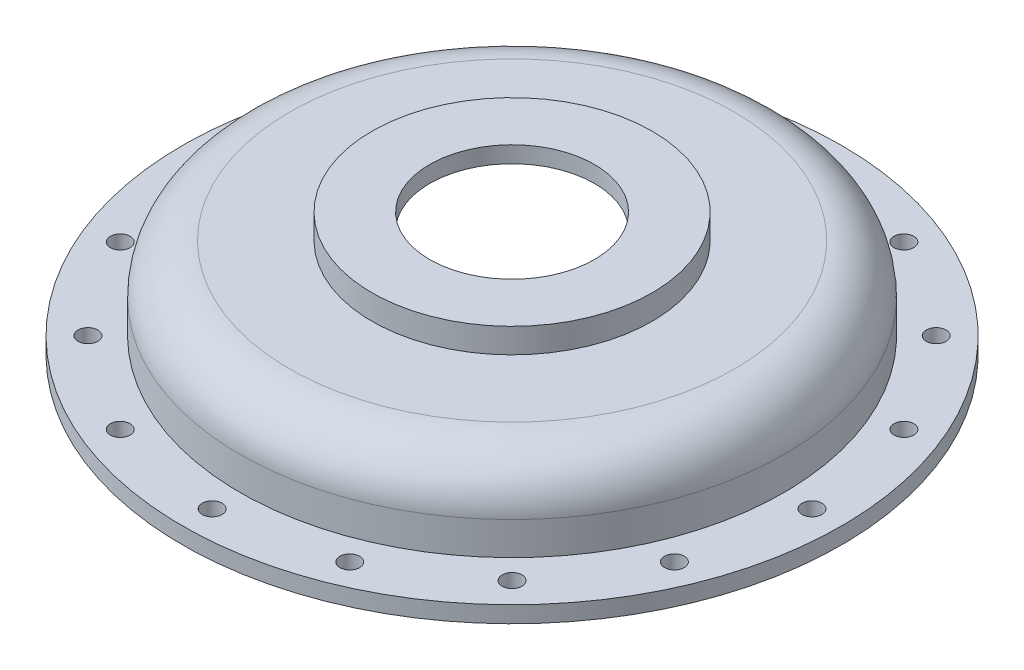
SolidWorks part; units mm, degrees
material "Brass"
ref_plane "Front Plane" through (0, 0, 0) normal (0, 0, 1) x (1, 0, 0)
ref_plane "Top Plane" through (0, 0, 0) normal (0, 1, 0) x (1, 0, 0)
ref_plane "Right Plane" through (0, 0, 0) normal (1, 0, 0) x (0, 0, -1)
sketch "Sketch2" plane through (0, 0, 0) normal (0, 0, 1) x (1, 0, 0)
  line L0 (0, 0) -> (0, 93.3105) construction
  line L1 (155, -56.5685) -> (200, -56.5685)
  line L2 (200, -56.5685) -> (200, -46.5685)
  line L3 (200, -46.5685) -> (165, -46.5685)
  line L4 (165, -46.5685) -> (165, -26.5685)
  line L5 (135, 3.4315) -> (85, 3.4315)
  line L6 (85, 3.4315) -> (85, 18.4315)
  line L7 (85, 18.4315) -> (0, 18.4315)
  line L8 (0, 8.4315) -> (75, 8.4315)
  line L9 (75, -6.5685) -> (75, 8.4315)
  line L10 (75, -6.5685) -> (134.2551, -6.5685)
  line L11 (155, -26.5685) -> (155, -56.5685)
  line L12 (0, 18.4315) -> (0, 8.4315)
  arc A0 (165, -26.5685) -> (135, 3.4315) centre (135, -26.5685) ccw
  arc A1 (134.2551, -6.5685) -> (155, -26.5685) centre (134.2551, -27.3274) cw
  dimension "D1" = 10
  dimension "D2" = 200
  dimension "D7" = 85
  dimension "D11" = 30
  dimension "D9" = 20.7588
  dimension "D3" = 10
  dimension "D4" = 165
  dimension "D5" = 15
  dimension "D6" = 10
  dimension "D8" = 10
  dimension "D10" = 75
  dimension "D12" = 10
revolve "Revolve1" add sketch "Sketch2" angle 360 about L0
sketch "Sketch3" plane through (0, -46.5685, 0) normal (0, 1, 0) x (1, 0, 0)
  circle A0 centre (0, 182) radius 6
  dimension "D2" = 12
  dimension "D1" = 182
extrude "Cut-Extrude1" cut sketch "Sketch3" against normal through all
pattern_circular "CirPattern1" count 16 over 360 about axis through (0, 0, 0) along (0, 1, 0) of "Cut-Extrude1"
sketch "Sketch4" plane through (0, 18.4315, 0) normal (0, 1, 0) x (1, 0, 0)
  circle A0 centre (0, 0) radius 50
  dimension "D1" = 100
extrude "Cut-Extrude2" cut sketch "Sketch4" along direction (0, 1, 0) on the side against the normal through all
